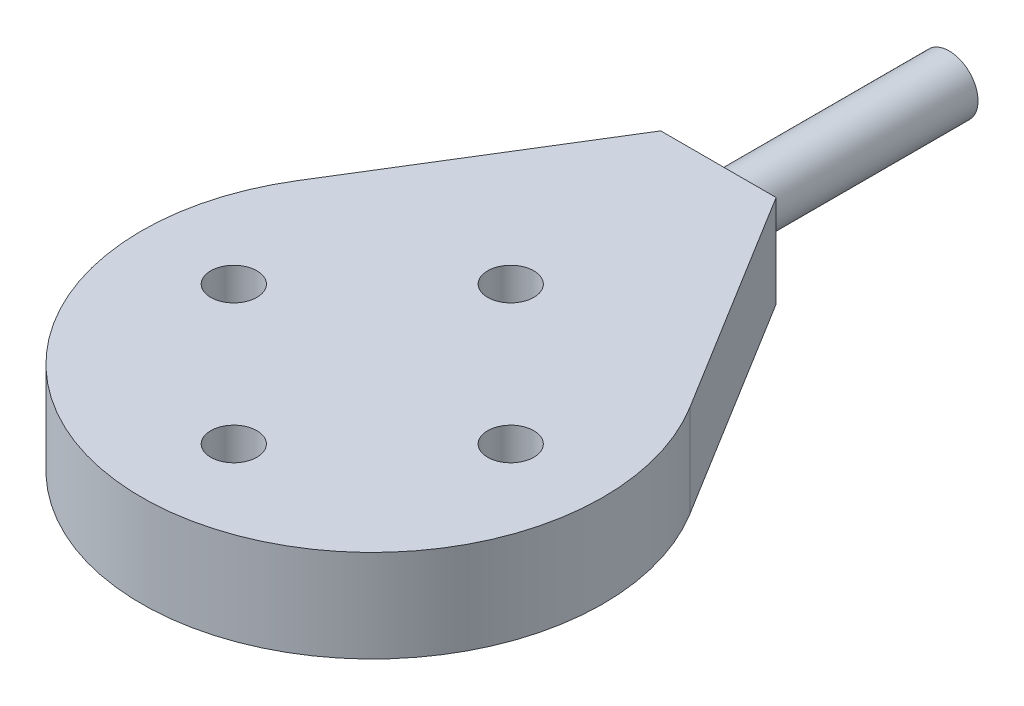
SolidWorks part; units mm, degrees
ref_plane "Front Plane" through (0, 0, 0) normal (0, 0, 1) x (1, 0, 0)
ref_plane "Top Plane" through (0, 0, 0) normal (0, 1, 0) x (1, 0, 0)
ref_plane "Right Plane" through (0, 0, 0) normal (1, 0, 0) x (0, 0, -1)
sketch "Sketch1" plane through (0, 0, 0) normal (0, 1, 0) x (1, 0, 0)
  line L0 (0, 7.62) -> (0, 0) construction
  line L1 (-10.8106, 6.6649) -> (-3.175, 19.05)
  line L2 (-3.175, 19.05) -> (3.175, 19.05)
  line L3 (3.175, 19.05) -> (10.8106, 6.6649)
  arc A0 (-10.8106, 6.6649) -> (10.8106, 6.6649) centre (0, 0) ccw
  circle A1 centre (0, 7.62) radius 1.27
  circle A2 centre (7.62, 0) radius 1.27
  circle A3 centre (0, -7.62) radius 1.27
  circle A4 centre (-7.62, 0) radius 1.27
  point P5 (-3.175, 19.6855)
  point P14 (0, 0)
  dimension "D1" = 2.54
  dimension "D3" = 25.4
  dimension "D2" = 7.62
  dimension "D5" = 6.35
  dimension "D6" = 19.05
  dimension "D4" = 4
extrude "Boss-Extrude1" add sketch "Sketch1" along normal blind 5.08
sketch "Sketch2" plane through (0, 0, -19.05) normal (0, 0, -1) x (-1, 0, 0)
  line L0 (-3.175, 2.54) -> (3.175, 2.54) construction
  line L1 (-3.175, 5.08) -> (-3.175, 0) construction
  line L2 (3.175, 5.08) -> (3.175, 0) construction
  line L3 (0, 5.08) -> (0, 0) construction
  line L4 (-3.175, 5.08) -> (3.175, 5.08) construction
  circle A1 centre (0, 2.54) radius 1.5875
  dimension "D1" = 3.175
extrude "Boss-Extrude2" add sketch "Sketch2" along normal blind 12.7
